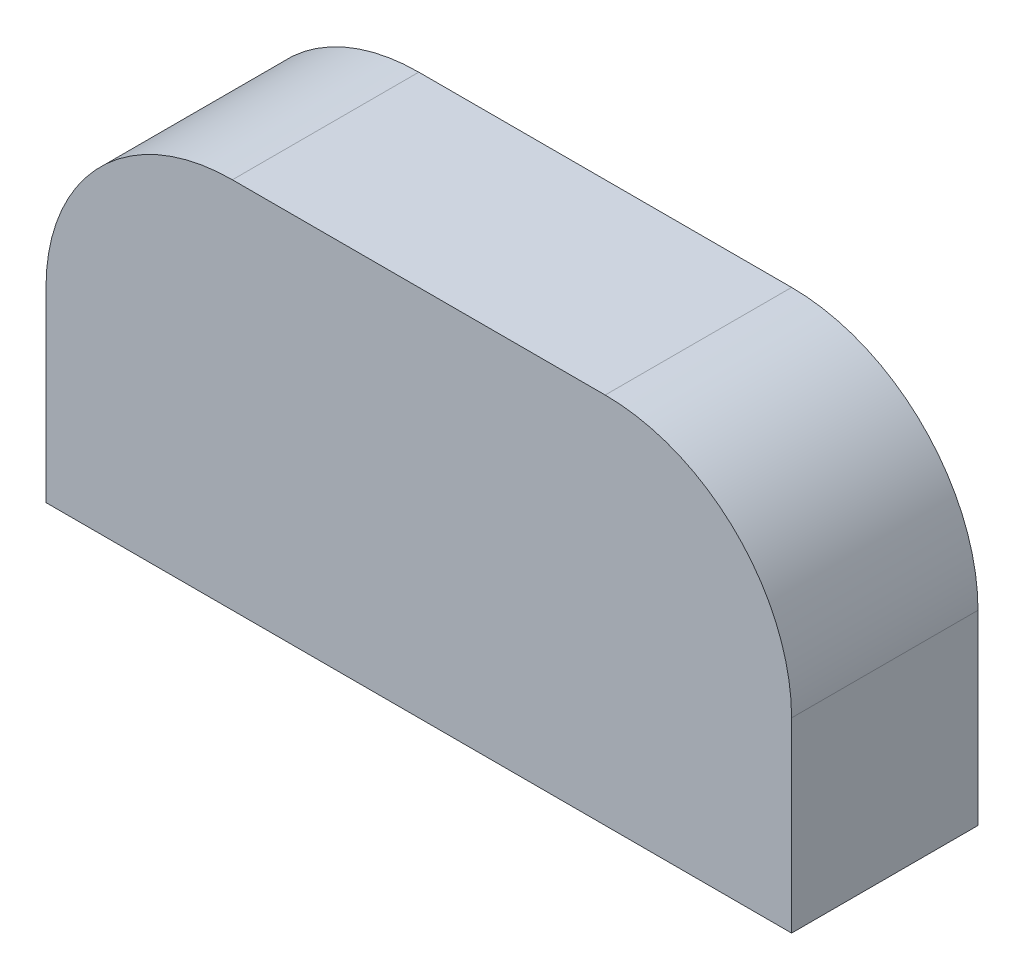
SolidWorks part; units mm, degrees
material "Pin"
ref_plane "Front" through (0, 0, 0) normal (0, 0, 1) x (1, 0, 0)
ref_plane "Top" through (0, 0, 0) normal (0, 1, 0) x (1, 0, 0)
ref_plane "Right" through (0, 0, 0) normal (1, 0, 0) x (0, 0, -1)
sketch "Esquisse2" plane through (0, 0, 0) normal (0, 0, 1) x (1, 0, 0)
  line L1 (-12.7, 6.35) -> (12.7, 6.35)
  line L2 (-12.7, 6.35) -> (-12.7, -6.35)
  line L3 (-12.7, -6.35) -> (12.7, -6.35)
  line L4 (12.7, 6.35) -> (12.7, -6.35)
  line L5 (-12.7, 6.35) -> (12.7, -6.35) construction
  line L6 (-12.7, -6.35) -> (12.7, 6.35) construction
  point P0 (0, 0)
  dimension "D1" = 12.7
  dimension "D2" = 25.4
extrude "Boss.-Extru.1" add sketch "Esquisse2" along normal blind 6.35
fillet "Congé1" radius 6.35 2 edges at (-12.7, 6.35, 3.175) (12.7, 6.35, 3.175)
